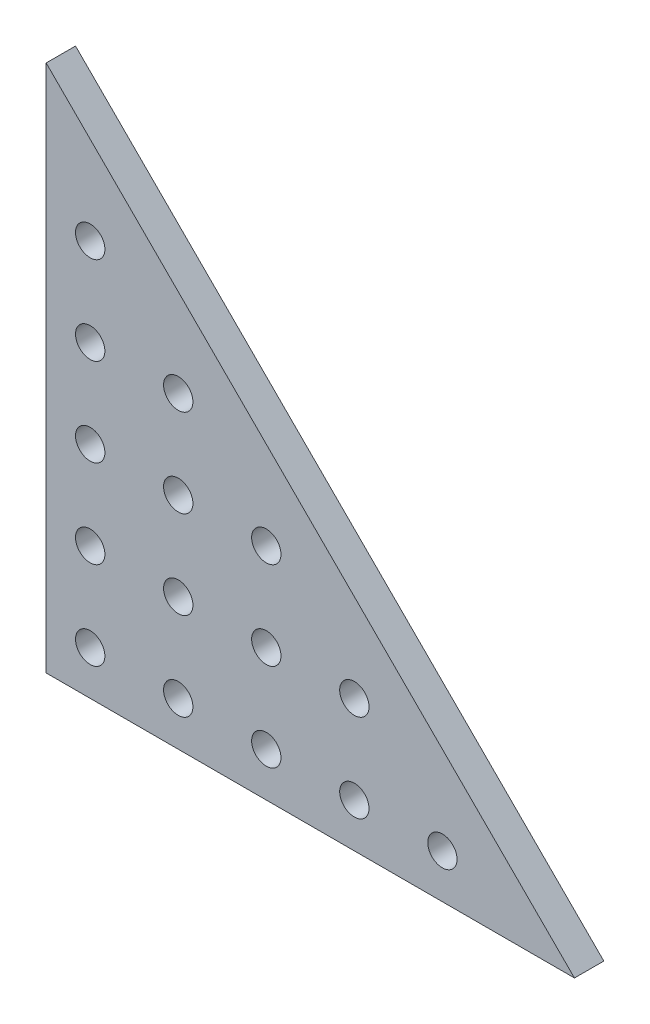
SolidWorks part; units mm, degrees
ref_plane "Alzado" through (0, 0, 0) normal (0, 0, 1) x (1, 0, 0)
ref_plane "Planta" through (0, 0, 0) normal (0, 1, 0) x (1, 0, 0)
ref_plane "Vista lateral" through (0, 0, 0) normal (1, 0, 0) x (0, 0, -1)
sketch "Model" plane through (0, 0, 0) normal (0, 0, 1) x (1, 0, 0)
  line L0 (-105.9434, 105.5565) -> (-105.9434, 51.5565)
  line L1 (-105.9434, 51.5565) -> (-51.9434, 51.5565)
  line L2 (-105.9434, 105.5565) -> (-51.9434, 51.5565)
  circle A0 centre (-101.4434, 92.0565) radius 1.5
  circle A1 centre (-101.4434, 83.0565) radius 1.5
  circle A2 centre (-92.4434, 83.0565) radius 1.5
  circle A3 centre (-101.4434, 74.0565) radius 1.5
  circle A4 centre (-92.4434, 74.0565) radius 1.5
  circle A5 centre (-83.4434, 74.0565) radius 1.5
  circle A6 centre (-101.4434, 65.0565) radius 1.5
  circle A7 centre (-92.4434, 65.0565) radius 1.5
  circle A8 centre (-83.4434, 65.0565) radius 1.5
  circle A9 centre (-74.4434, 65.0565) radius 1.5
  circle A10 centre (-101.4434, 56.0565) radius 1.5
  circle A11 centre (-92.4434, 56.0565) radius 1.5
  circle A12 centre (-83.4434, 56.0565) radius 1.5
  circle A13 centre (-74.4434, 56.0565) radius 1.5
  circle A14 centre (-65.4434, 56.0565) radius 1.5
extrude "Saliente-Extruir1" add sketch "Model" along normal blind 3
